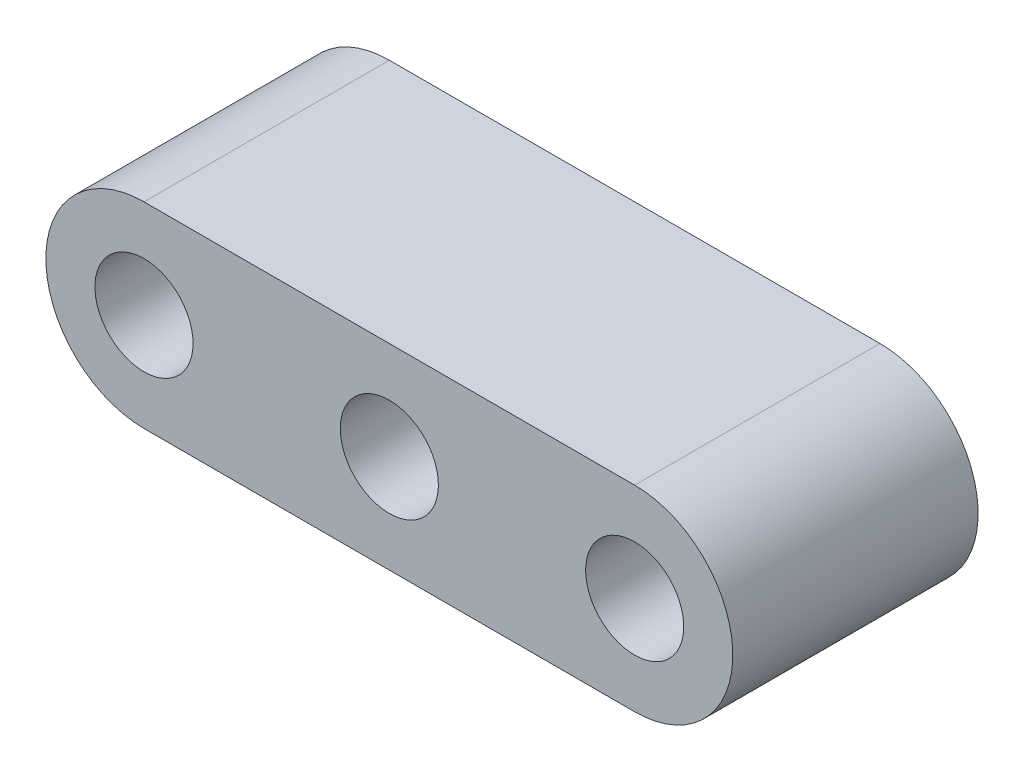
SolidWorks part; units mm, degrees
ref_plane "前视基准面" through (0, 0, 0) normal (0, 0, 1) x (1, 0, 0)
ref_plane "上视基准面" through (0, 0, 0) normal (0, 1, 0) x (1, 0, 0)
ref_plane "右视基准面" through (0, 0, 0) normal (1, 0, 0) x (0, 0, -1)
sketch "草图1" plane through (0, 0, 0) normal (0, 0, 1) x (1, 0, 0)
  line L0 (0, 0) -> (3.0745, 0) construction
  line L1 (3.0745, 0) -> (-2.9701, 0) construction
  line L2 (0, 0) -> (0, 2.0702) construction
  line L3 (0, 2.0702) -> (0, -1.9657) construction
  line L4 (-10, 4) -> (10, 4)
  line L5 (-10, -4) -> (10, -4)
  circle A0 centre (-10, 0) radius 2
  arc A1 (-10, 4) -> (-10, -4) centre (-10, 0) ccw
  circle A2 centre (10, 0) radius 2
  arc A3 (10, 4) -> (10, -4) centre (10, 0) cw
  circle A4 centre (0, 0) radius 2
  dimension "D1" = 4
  dimension "D2" = 8
  dimension "D3" = 10
extrude "凸台-拉伸1" add sketch "草图1" along normal blind 10
